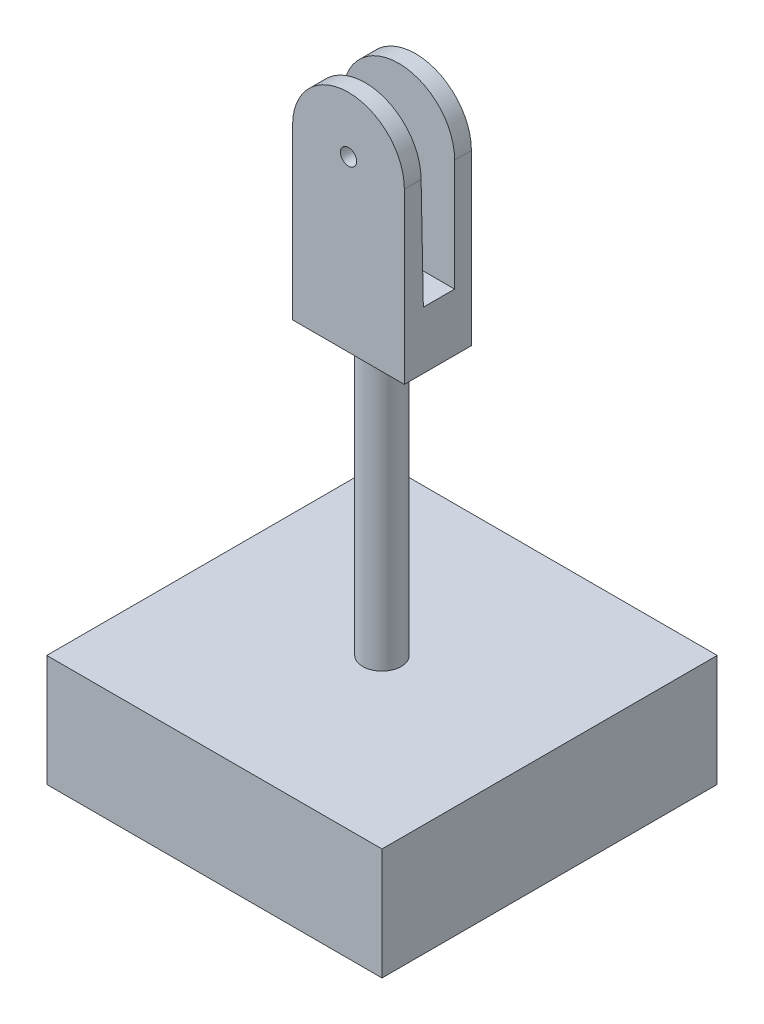
SolidWorks part; units mm, degrees
ref_plane "前基準面" through (0, 0, 0) normal (0, 0, 1) x (1, 0, 0)
ref_plane "上基準面" through (0, 0, 0) normal (0, 1, 0) x (1, 0, 0)
ref_plane "右基準面" through (0, 0, 0) normal (1, 0, 0) x (0, 0, -1)
sketch "草圖1" plane through (0, 0, 0) normal (0, 0, 1) x (1, 0, 0)
  line L0 (0, 0) -> (0, -11.05)
  line L1 (-10, 0) -> (-10, -30.2764)
  line L3 (10, -30.2764) -> (10, 0)
  line L4 (-10, -30.2764) -> (10, -30.2764)
  circle A1 centre (0, 0) radius 1.45
  arc A2 (10, 0) -> (-10, 0) centre (0, 0) ccw
  dimension "D1" = 11.05
  dimension "D2" = 2.9
  dimension "D3" = 20
extrude "填料-伸長1" add sketch "草圖1" along normal blind 12
sketch "草圖2" plane through (10, 0, 0) normal (1, 0, 0) x (0, 0, -1)
  line L0 (-12, 0) -> (-9.1, 0)
  line L1 (-12, 0) -> (0, 0) construction
  line L2 (-12, 10) -> (-12, 0) construction
  line L3 (0, 0) -> (-2.9, 0)
  line L4 (-6, 0) -> (-3, 0)
  line L5 (-6, 0) -> (-9, 0)
  line L6 (-9, 0) -> (-9, 15.7808)
  line L7 (-9, 15.7808) -> (-3, 15.7808)
  line L8 (-3, 15.7808) -> (-3, 0)
  line L9 (-3, 0) -> (-3, -20)
  line L10 (-9, 0) -> (-8.6005, -20)
  line L11 (-8.6005, -20) -> (-3, -20)
  line M8 (0, 0) -> (-12, 0)
  dimension "D1" = 2.9
  dimension "D2" = 2.9
  dimension "D3" = 3
  dimension "D4" = 3
  dimension "D5" = 20
extrude "除料-伸長1" cut sketch "草圖2" against normal through all contours L8 L7 L6 M8 | L10 L11 L9 M8
sketch "草圖3" plane through (0, -30.2764, 0) normal (0, -1, 0) x (1, 0, 0)
  line L0 (10, 6) -> (-10, 6)
  line L1 (10, 12) -> (10, 0) construction
  line L2 (-10, 12) -> (-10, 0) construction
  circle A0 centre (0, 6) radius 3.45
  dimension "D1" = 6.9
extrude "填料-伸長2" add sketch "草圖3" along normal blind 50 contours L0 A0 | L0 A0
sketch "草圖4" plane through (0, -80.2764, 0) normal (0, -1, 0) x (1, 0, 0)
  line L0 (3.45, 6) -> (-3.45, 6)
  line L2 (30, 36) -> (-30, 36)
  line L3 (30, 36) -> (30, -24)
  line L4 (30, -24) -> (-30, -24)
  line L5 (-30, 36) -> (-30, -24)
  line L6 (30, 36) -> (-30, -24) construction
  line L7 (30, -24) -> (-30, 36) construction
  circle A0 centre (0, 6) radius 3.45 construction
  point P4 (0, 6)
  circle M3 centre (0, 6) radius 3.45
  dimension "D1" = 60
  dimension "D2" = 60
extrude "填料-伸長3" add sketch "草圖4" along normal blind 20 separate body contours L2 L5 L4 L3 M3
